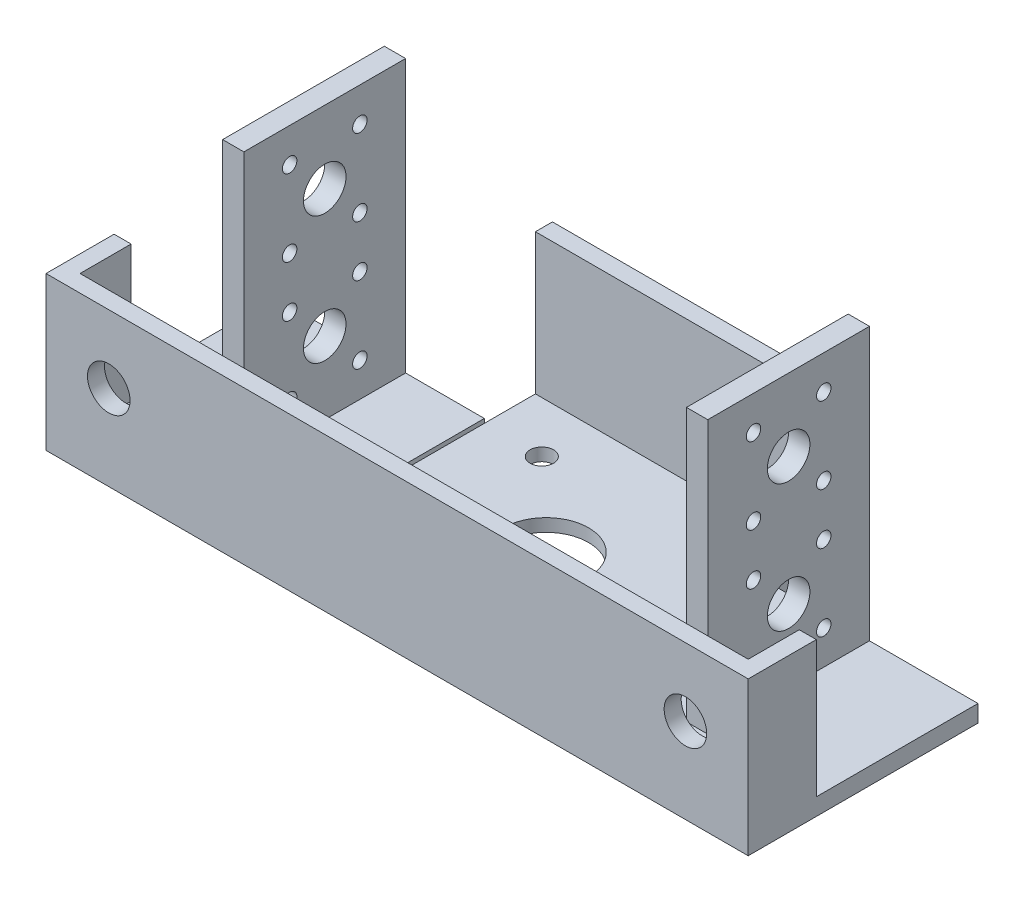
SolidWorks part; units mm, degrees
ref_plane "Front Plane" through (0, 0, 0) normal (0, 0, 1) x (1, 0, 0)
ref_plane "Top Plane" through (0, 0, 0) normal (0, 1, 0) x (1, 0, 0)
ref_plane "Right Plane" through (0, 0, 0) normal (1, 0, 0) x (0, 0, -1)
sketch "Sketch1" plane through (0, 0, 0) normal (0, 1, 0) x (1, 0, 0)
  line L0 (0, 0) -> (0, -14.43) construction
  line L1 (-37.5, 20) -> (37.5, 20)
  line L2 (-37.5, 20) -> (-37.5, -20)
  line L3 (-37.5, -20) -> (37.5, -20)
  line L4 (37.5, 20) -> (37.5, -20)
  line L5 (-37.5, 20) -> (37.5, -20) construction
  line L6 (-37.5, -20) -> (37.5, 20) construction
  line L7 (0, 0) -> (6.508, 0) construction
  line L8 (-5, 10) -> (5, 10)
  line L9 (-5, 10) -> (-5, -10)
  line L10 (-5, -10) -> (5, -10)
  line L11 (5, 10) -> (5, -10)
  line L12 (-5, 10) -> (5, -10) construction
  line L13 (-5, -10) -> (5, 10) construction
  circle A0 centre (-21, 0) radius 5
  circle A1 centre (-30, 8.25) radius 1.7
  circle A2 centre (-12, 8.25) radius 1.7
  circle A3 centre (-12, -8.25) radius 1.7
  circle A4 centre (-30, -8.25) radius 1.7
  circle A5 centre (12, 8.25) radius 1.7
  circle A6 centre (12, -8.25) radius 1.7
  circle A7 centre (21, 0) radius 5
  circle A8 centre (30, -8.25) radius 1.7
  circle A9 centre (30, 8.25) radius 1.7
  point P0 (0, 0)
  dimension "D3" = 10
  dimension "D4" = 16.5
  dimension "D5" = 16.5
  dimension "D6" = 18
  dimension "D9" = 10
  dimension "D11" = 20
  dimension "D13" = 7.5
  dimension "D17" = 3.4
  dimension "D19" = 11.75
  dimension "D20" = 11.75
  dimension "D1" = 75
  dimension "D2" = 40
  dimension "D10" = 10
  dimension "D7" = 2
  dimension "D8" = 2
extrude "Boss-Extrude1" add sketch "Sketch1" along normal blind 3
sketch "Sketch2" plane through (0, 3, 0) normal (0, 1, 0) x (1, 0, 0)
  line L0 (-37.5, 20) -> (-37.5, -20) construction
  line L1 (-33.5, 14) -> (33.5, 14)
  line L2 (-33.5, 14) -> (-33.5, -14)
  line L3 (-33.5, -14) -> (33.5, -14)
  line L4 (33.5, 14) -> (33.5, -14)
  line L5 (37.5, -20) -> (37.5, 20) construction
  line L6 (37.5, 20) -> (-37.5, 20) construction
  line L7 (-37.5, -20) -> (37.5, -20) construction
  dimension "D1" = 4
  dimension "D2" = 4
  dimension "D3" = 6
  dimension "D4" = 6
extrude "Cut-Extrude1" cut sketch "Sketch2" against normal through all both and the other way through all
sketch "Sketch3" plane through (0, 3, 0) normal (0, 1, 0) x (1, 0, 0)
  line L1 (37.5, 20) -> (-37.5, 20)
  line L2 (37.5, 20) -> (37.5, 35)
  line L3 (37.5, 35) -> (-37.5, 35)
  line L4 (-37.5, 20) -> (-37.5, 35)
  line L5 (-37.5, -20) -> (37.5, -20)
  line L6 (-37.5, -20) -> (-37.5, -35)
  line L7 (-37.5, -35) -> (37.5, -35)
  line L8 (37.5, -20) -> (37.5, -35)
  line L10 (-37.5, 20) -> (-33.5, 20)
  line L11 (-37.5, 20) -> (-37.5, -20)
  line L12 (-37.5, -20) -> (-33.5, -20)
  line L13 (-33.5, 20) -> (-33.5, -20)
  line L14 (37.5, 20) -> (33.5, 20)
  line L15 (37.5, 20) -> (37.5, -20)
  line L16 (37.5, -20) -> (33.5, -20)
  line L17 (33.5, 20) -> (33.5, -20)
  line M3 (-33.5, -14) -> (-33.5, 14)
  line M5 (33.5, 14) -> (33.5, -14)
  line M11 (37.5, -20) -> (37.5, 20)
  line M12 (37.5, 20) -> (-37.5, 20)
  line M13 (-37.5, 20) -> (-37.5, -20)
  line M14 (-37.5, -20) -> (37.5, -20)
  dimension "D1" = 15
  dimension "D2" = 15
extrude "Boss-Extrude3" add sketch "Sketch3" along normal blind 110 and the other way blind 3 contours L8 L5 L6 L7 M14 | L4 L1 L2 L3 M12 | L17 M12 M5 M14 M11 | L13 L1 M13 M14 M3
sketch "Sketch6" plane through (0, 3, 0) normal (0, 1, 0) x (1, 0, 0)
  line L0 (-37.5, -35) -> (37.5, -35) construction
  line L1 (-33.5, -20) -> (33.5, -20)
  line L2 (-33.5, -20) -> (-33.5, -31)
  line L3 (-33.5, -31) -> (33.5, -31)
  line L4 (33.5, -20) -> (33.5, -31)
  line L5 (33.5, 20) -> (-33.5, 20)
  line L6 (33.5, 20) -> (33.5, 31)
  line L7 (33.5, 31) -> (-33.5, 31)
  line L8 (-33.5, 20) -> (-33.5, 31)
  line L9 (37.5, 35) -> (-37.5, 35) construction
  dimension "D1" = 4
  dimension "D2" = 4
extrude "Cut-Extrude4" cut sketch "Sketch6" along normal through all
sketch "Sketch7" plane through (-37.5, 0, 0) normal (-1, 0, 0) x (0, 0, 1)
  line L0 (35, 0) -> (35, 113) construction
  line L1 (-35, 113) -> (35, 113)
  line L2 (-35, 113) -> (-35, 76)
  line L3 (-35, 76) -> (35, 76)
  line L4 (35, 113) -> (35, 76)
  dimension "D1" = 37
extrude "Boss-Extrude4" add sketch "Sketch7" along normal blind 45
ref_plane "Plane1" through (0, 0, 0) normal (1, 0, 0) x (0, 0, -1)
mirror "Mirror2" about plane through (0, 0, 0) normal (1, 0, 0) of "Boss-Extrude4"
sketch "Sketch8" plane through (0, 113, 0) normal (0, 1, 0) x (1, 0, 0)
  line L0 (-82.5, -35) -> (-82.5, 35) construction
  line L1 (-33.5, 31) -> (-78.5, 31)
  line L2 (-33.5, 31) -> (-33.5, -31)
  line L3 (-33.5, -31) -> (-78.5, -31)
  line L4 (-78.5, 31) -> (-78.5, -31)
  line L5 (33.5, -31) -> (78.5, -31)
  line L6 (33.5, -31) -> (33.5, 31)
  line L7 (33.5, 31) -> (78.5, 31)
  line L8 (78.5, -31) -> (78.5, 31)
  line L9 (82.5, -35) -> (82.5, 35) construction
  dimension "D1" = 4
  dimension "D2" = 4
extrude "Cut-Extrude6" cut sketch "Sketch8" against normal blind 29
sketch "Sketch9" plane through (-82.5, 0, 0) normal (-1, 0, 0) x (0, 0, 1)
  line L18 (-31, 84) -> (31, 84) construction
  line L19 (-19, 84) -> (19, 84)
  line L20 (-19, 84) -> (-19, 112.5)
  line L21 (-19, 112.5) -> (19, 112.5)
  line L22 (19, 84) -> (19, 112.5)
  line L25 (-31, 84) -> (-31, 113) construction
  dimension "D1" = 38
  dimension "D2" = 12
  dimension "D3" = 28.5
sketch "Sketch11" plane through (0, 0, 35) normal (0, 0, 1) x (1, 0, 0)
  line L0 (82.5, 76) -> (82.5, 113) construction
  line L1 (-82.5, 76) -> (-37.5, 76)
  line L2 (-82.5, 76) -> (-82.5, 80)
  line L3 (-82.5, 80) -> (-37.5, 80)
  line L4 (-37.5, 76) -> (-37.5, 80)
  line L5 (37.5, 76) -> (82.5, 76)
  line L6 (37.5, 76) -> (37.5, 80)
  line L7 (37.5, 80) -> (82.5, 80)
  line L8 (82.5, 76) -> (82.5, 80)
  line L11 (-78.5, 84) -> (-33.5, 84) construction
  line L12 (33.5, 84) -> (78.5, 84) construction
  dimension "D1" = 4
  dimension "D2" = 4
extrude "Cut-Extrude9" cut sketch "Sketch11" against normal through all
extrude "Cut-Extrude10" cut sketch "Sketch9" against normal through all
sketch "Sketch13" plane through (0, 84, 0) normal (0, 1, 0) x (1, 0, 0)
  line L0 (-78.5, 31) -> (-78.5, -31) construction
  line L1 (-57, 19) -> (-52, 19)
  line L2 (-57, 19) -> (-57, -19)
  line L3 (-57, -19) -> (-52, -19)
  line L4 (-52, 19) -> (-52, -19)
  line L7 (78.5, 31) -> (-78.5, 31) construction
  line L13 (-57, -19) -> (-57, 19)
  line L17 (-82.5, -19) -> (-107.5, -19)
  line L18 (-82.5, -19) -> (-82.5, 19)
  line L19 (-82.5, 19) -> (-107.5, 19)
  line L20 (-107.5, -19) -> (-107.5, 19)
  line L21 (-107.5, 19) -> (-61, 19)
  line L22 (-107.5, 19) -> (-107.5, -19)
  line L23 (-107.5, -19) -> (-61, -19)
  line L24 (-61, 19) -> (-61, -19)
  dimension "D1" = 21.5
  dimension "D2" = 5
  dimension "D3" = 38
  dimension "D4" = 12
  dimension "D5" = 25
  dimension "D6" = 46.5
extrude "Boss-Extrude5" add sketch "Sketch13" along normal blind 32 contours L4 L1 L2 L3
sketch "Sketch14" plane through (-57, 0, 0) normal (-1, 0, 0) x (0, 0, 1)
  line L0 (-19, 116) -> (-19, 84) construction
  line L4 (19, 112.5) -> (-19, 112.5) construction
  circle A0 centre (0, 101) radius 5
  circle A1 centre (-8.25, 110) radius 1.7
  circle A2 centre (8.25, 110) radius 1.7
  circle A3 centre (8.25, 92) radius 1.7
  circle A4 centre (-8.25, 92) radius 1.7
  dimension "D1" = 19
  dimension "D2" = 8.25
  dimension "D3" = 10
  dimension "D6" = 3.4
  dimension "D7" = 11.5
  dimension "D8" = 18
  dimension "D9" = 16.5
  dimension "D10" = 9
  dimension "D11" = 8.25
  dimension "D4" = 2
  dimension "D5" = 2
extrude "Cut-Extrude11" cut sketch "Sketch14" against normal blind 32
mirror "Mirror4" about plane through (0, 0, 0) normal (1, 0, 0) of "Boss-Extrude5", "Cut-Extrude11"
sketch "Sketch15" plane through (0, 113, 0) normal (0, 1, 0) x (1, 0, 0)
  line L1 (-82.5, 35) -> (82.5, 35)
  line L2 (-82.5, 35) -> (-82.5, -35)
  line L3 (-82.5, -35) -> (82.5, -35)
  line L4 (82.5, 35) -> (82.5, -35)
  line L5 (-78.5, 31) -> (78.5, 31)
  line L6 (-78.5, 31) -> (-78.5, -31)
  line L7 (-78.5, -31) -> (78.5, -31)
  line L8 (78.5, 31) -> (78.5, -31)
extrude "Boss-Extrude6" add sketch "Sketch15" along normal blind 3
sketch "Sketch16" plane through (0, 0, 35) normal (0, 0, 1) x (1, 0, 0)
  line L1 (-10, 14.0464) -> (10, 14.0464)
  line L2 (-10, 14.0464) -> (-10, 9.2258)
  line L3 (-10, 9.2258) -> (10, 9.2258)
  line L4 (10, 14.0464) -> (10, 9.2258)
  line L5 (-37.5, 0) -> (-37.5, 80) construction
  dimension "D1" = 20
  dimension "D2" = 27.5
extrude "Cut-Extrude12" cut sketch "Sketch16" against normal through all
sketch "Sketch18" plane through (0, 0, 35) normal (0, 0, 1) x (1, 0, 0)
  line L0 (57, 116) -> (57, 84) construction
  line L2 (33.5, 84) -> (78.5, 84) construction
  circle A0 centre (67.75, 100) radius 5
  dimension "D1" = 10.75
  dimension "D2" = 16
  dimension "D3" = 10
extrude "Cut-Extrude14" cut sketch "Sketch18" against normal through all
mirror "Mirror5" about plane through (0, 0, 0) normal (1, 0, 0) of "Cut-Extrude14"
mirror "Mirror6" about plane through (0, 116, 0) normal (0, 1, 0) of "Mirror4", "Boss-Extrude5", "Cut-Extrude11"
sketch "Sketch19" plane through (82.5, 0, 0) normal (1, 0, 0) x (0, 0, -1)
  line L0 (19, 148) -> (19, 84) construction
  line L1 (-19, 112.5) -> (19, 112.5)
  line L2 (-19, 112.5) -> (-19, 116)
  line L3 (-19, 116) -> (19, 116)
  line L4 (19, 112.5) -> (19, 116)
extrude "Cut-Extrude15" cut sketch "Sketch19" against normal blind 10
mirror "Mirror7" about plane through (0, 0, 0) normal (1, 0, 0) of "Cut-Extrude15"
sketch "Sketch20" plane through (0, 3, 0) normal (0, 1, 0) x (1, 0, 0)
  line L0 (33.5, 31) -> (-33.5, 31) construction
  line L1 (-5, -10) -> (5, -10)
  line L2 (-5, -10) -> (-5, 10)
  line L3 (-5, 10) -> (5, 10)
  line L4 (5, -10) -> (5, 10)
  line L5 (-5, -10) -> (5, 10) construction
  line L6 (-5, 10) -> (5, -10) construction
  line L7 (0, 0) -> (0, 17.5) construction
  line L8 (-37.5, 20) -> (37.5, 20)
  line L9 (-37.5, 20) -> (-37.5, -20)
  line L10 (-37.5, -20) -> (37.5, -20)
  line L11 (37.5, 20) -> (37.5, -20)
  line L12 (-37.5, 20) -> (37.5, -20) construction
  line L13 (-37.5, -20) -> (37.5, 20) construction
  line L14 (0, -34.1) -> (0, 34.1) construction
  circle A1 centre (-12, 17.5) radius 1.2
  circle A2 centre (-12, -17.5) radius 1.2
  circle A3 centre (-24, -17.5) radius 1.2
  circle A4 centre (-24, 17.5) radius 1.2
  circle A5 centre (12, -17.5) radius 1.2
  circle A6 centre (24, -17.5) radius 1.2
  circle A7 centre (12, 17.5) radius 1.2
  circle A8 centre (24, 17.5) radius 1.2
  point P2 (0, 0)
  point P10 (0, 0)
  dimension "D1" = 7
  dimension "D2" = 10
  dimension "D4" = 2.5
  dimension "D7" = 35
  dimension "D8" = 7
  dimension "D9" = 2.4
  dimension "D11" = 12
  dimension "D3" = 21
  dimension "D5" = 75
  dimension "D6" = 40
  dimension "D10" = 2
extrude "Cut-Extrude16" cut sketch "Sketch20" against normal blind 10 contours A4 | A1 | A7 | A3 | A2 | A8 | A5 | A6
sketch "Sketch21" plane through (0, 0, 35) normal (0, 0, 1) x (1, 0, 0)
  line L0 (0, -34.1) -> (0, 34.1) construction
  line L1 (37.5, 0) -> (27.5, 0)
  line L2 (37.5, 0) -> (37.5, 80)
  line L3 (37.5, 80) -> (27.5, 80)
  line L4 (27.5, 0) -> (27.5, 80)
  line L5 (-27.5, 0) -> (-27.5, 80)
  line L6 (-37.5, 80) -> (-27.5, 80)
  line L7 (-37.5, 0) -> (-37.5, 80)
  line L8 (-37.5, 0) -> (-27.5, 0)
  dimension "D1" = 10
  dimension "D2" = 80
extrude "Cut-Extrude17" cut sketch "Sketch21" against normal through all
sketch "Sketch22" plane through (0, 0, 35) normal (0, 0, 1) x (1, 0, 0)
  line L1 (-27.5, 0) -> (27.5, 0)
  line L2 (-27.5, 0) -> (-27.5, 80)
  line L3 (-27.5, 80) -> (27.5, 80)
  line L4 (27.5, 0) -> (27.5, 80)
extrude "Cut-Extrude18" cut sketch "Sketch22" against normal through all
sketch "Sketch23" plane through (0, 80, 0) normal (0, -1, 0) x (1, 0, 0)
  line L1 (-33.5, 31) -> (33.5, 31)
  line L2 (-33.5, 31) -> (-33.5, -31)
  line L3 (-33.5, -31) -> (33.5, -31)
  line L4 (33.5, 31) -> (33.5, -31)
extrude "Boss-Extrude7" add sketch "Sketch23" against normal blind 3
sketch "Sketch24" plane through (0, 83, 0) normal (0, 1, 0) x (1, 0, 0)
  line L5 (78.5, 31) -> (-78.5, 31) construction
  line L9 (33.5, -31) -> (-33.5, -31) construction
  line L10 (0, 0) -> (0, 16.8876) construction
  line L11 (0, -34.1) -> (0, 34.1) construction
  circle A0 centre (0, 0) radius 10
  circle A1 centre (-20, 19) radius 2.75
  circle A2 centre (-20, -19) radius 2.75
  circle A3 centre (20, -19) radius 2.75
  circle A4 centre (20, 19) radius 2.75
  dimension "D1" = 20
  dimension "D2" = 12
  dimension "D3" = 20
  dimension "D4" = 12
extrude "Cut-Extrude19" cut sketch "Sketch24" against normal through all
sketch "Sketch25" plane through (0, 0, -35) normal (0, 0, -1) x (-1, 0, 0)
  line L0 (33.5, 84) -> (33.5, 80)
  line L5 (-82.5, 80) -> (82.5, 80) construction
  line L7 (33.5, 80) -> (82.5, 80)
  line L8 (33.5, 80) -> (33.5, 116)
  line L9 (33.5, 116) -> (82.5, 116)
  line L10 (82.5, 80) -> (82.5, 116)
  line M2 (-82.5, 80) -> (82.5, 80)
  line M3 (82.5, 80) -> (82.5, 116)
  line M4 (82.5, 116) -> (-82.5, 116)
  circle M5 centre (67.75, 100) radius 5
extrude "Cut-Extrude21" cut sketch "Sketch25" against normal blind 16 contours L8 L0 M2 M3 M4 M5
mirror "Mirror8" about plane through (0, 0, 0) normal (1, 0, 0) of "Cut-Extrude21"
